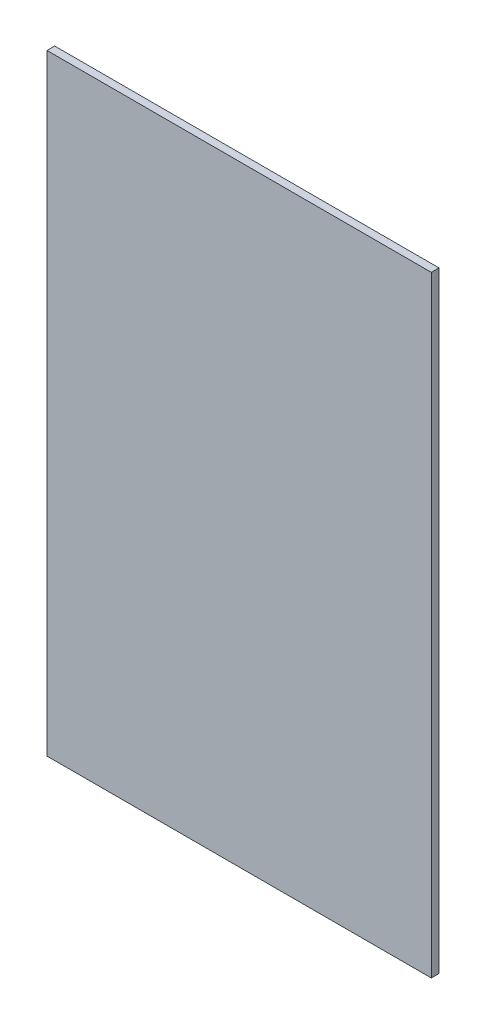
SolidWorks part; units mm, degrees
ref_plane "Plan de face" through (0, 0, 0) normal (0, 0, 1) x (1, 0, 0)
ref_plane "Plan de dessus" through (0, 0, 0) normal (0, 1, 0) x (1, 0, 0)
ref_plane "Plan de droite" through (0, 0, 0) normal (1, 0, 0) x (0, 0, -1)
sketch "Esquisse1" plane through (0, 0, 0) normal (0, 0, 1) x (1, 0, 0)
  line L1 (-50, 79.5) -> (50, 79.5)
  line L2 (-50, 79.5) -> (-50, -79.5)
  line L3 (-50, -79.5) -> (50, -79.5)
  line L4 (50, 79.5) -> (50, -79.5)
  line L5 (-50, 79.5) -> (50, -79.5) construction
  line L6 (-50, -79.5) -> (50, 79.5) construction
  point P0 (0, 0)
  dimension "D1" = 100
  dimension "D2" = 159
extrude "Boss.-Extru.1" add sketch "Esquisse1" along normal blind 2
